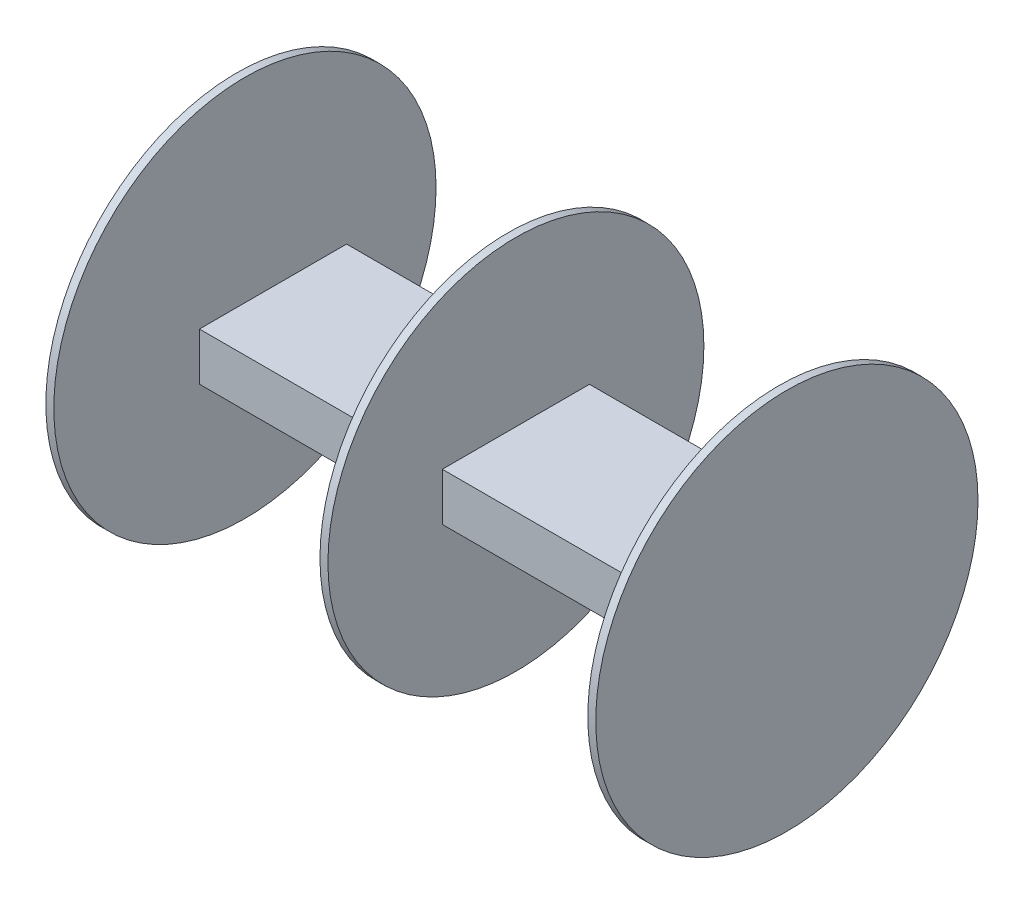
SolidWorks part; units mm, degrees
ref_plane "Front Plane" through (0, 0, 0) normal (0, 0, 1) x (1, 0, 0)
ref_plane "Top Plane" through (0, 0, 0) normal (0, 1, 0) x (1, 0, 0)
ref_plane "Right Plane" through (0, 0, 0) normal (1, 0, 0) x (0, 0, -1)
sketch "Sketch2" plane through (0, 0, 0) normal (1, 0, 0) x (0, 0, -1)
  circle A0 centre (0, 0) radius 304.8
  dimension "D1" = 609.6
extrude "Boss-Extrude1" add sketch "Sketch2" along normal blind 12.7
sketch "Sketch3" plane through (0, 0, 0) normal (0, 1, 0) x (1, 0, 0)
  line L1 (-806.7969, 117.3332) -> (-44.7969, 117.3332)
  line L2 (-806.7969, 117.3332) -> (-806.7969, -117.3332)
  line L3 (-806.7969, -117.3332) -> (-44.7969, -117.3332)
  line L4 (-44.7969, 117.3332) -> (-44.7969, -117.3332)
  point P4 (-44.7969, 0)
  dimension "D1" = 762
extrude "Boss-Extrude2" add sketch "Sketch3" along normal mid plane 76.2 separate body
ref_plane "Plane1" through (-425.7969, 0, 0) normal (-1, 0, 0) x (0, 0, 1)
sketch "Sketch4" plane through (-425.7969, 0, 0) normal (-1, 0, 0) x (0, 0, 1)
  circle A0 centre (0, 0) radius 299.8
  circle A1 centre (0, 0) radius 304.8 construction
  dimension "D1" = 5
extrude "Boss-Extrude3" add sketch "Sketch4" along normal mid plane 12.7 separate body
mirror "Mirror1" about plane through (-425.7969, 0, 0) normal (-1, 0, 0) of bodies 101
